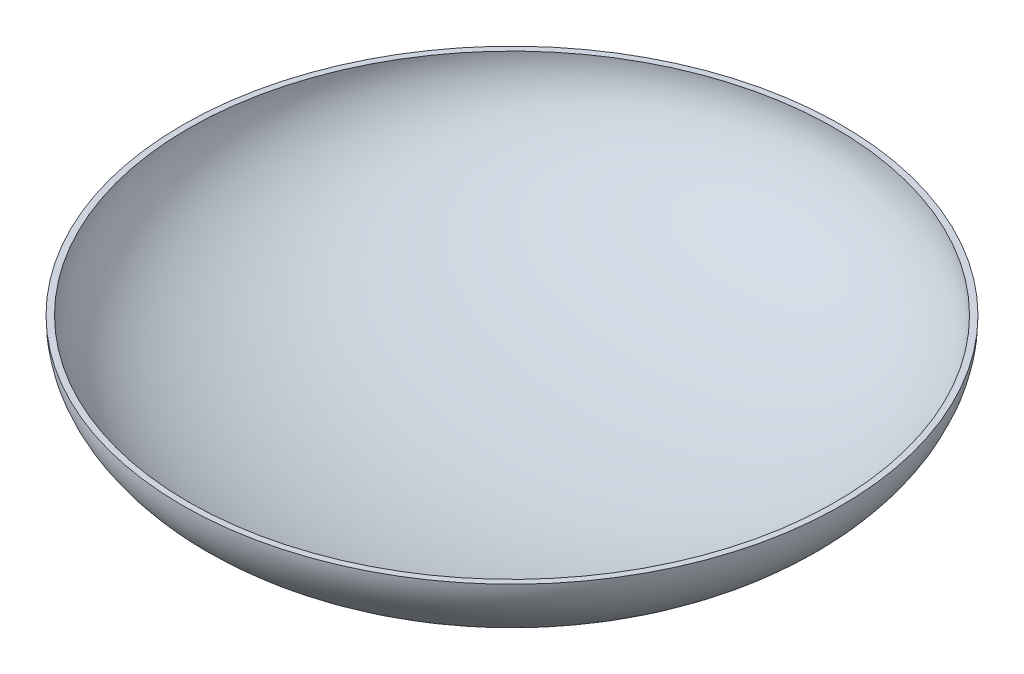
SolidWorks part; units mm, degrees
ref_plane "Front Plane" through (0, 0, 0) normal (0, 0, 1) x (1, 0, 0)
ref_plane "Top Plane" through (0, 0, 0) normal (0, 1, 0) x (1, 0, 0)
ref_plane "Right Plane" through (0, 0, 0) normal (1, 0, 0) x (0, 0, -1)
sketch "Sketch1" plane through (0, 0, 0) normal (0, 0, 1) x (1, 0, 0)
  line L0 (0, -61.8724) -> (-137.16, -61.8724) construction
  line L1 (-137.16, -61.8724) -> (-139.7, -61.8724)
  line L2 (0, -117.7524) -> (0, -61.8724) construction
  line L3 (0, -117.7524) -> (0, -120.2924)
  ellipse E0 centre (0, -61.8724) end of major axis (137.16, -61.8724) minor radius 55.88 (-137.16, -61.8724) -> (0, -117.7524) ccw
  ellipse E1 centre (0, -61.8724) end of major axis (139.7, -61.8724) minor radius 58.42 (-139.7, -61.8724) -> (0, -120.2924) ccw
  dimension "D1" = 137.16
  dimension "D2" = 55.88
  dimension "D3" = 2.54
  dimension "D4" = 2.54
revolve "Revolve1" add sketch "Sketch1" angle 360 about L3
